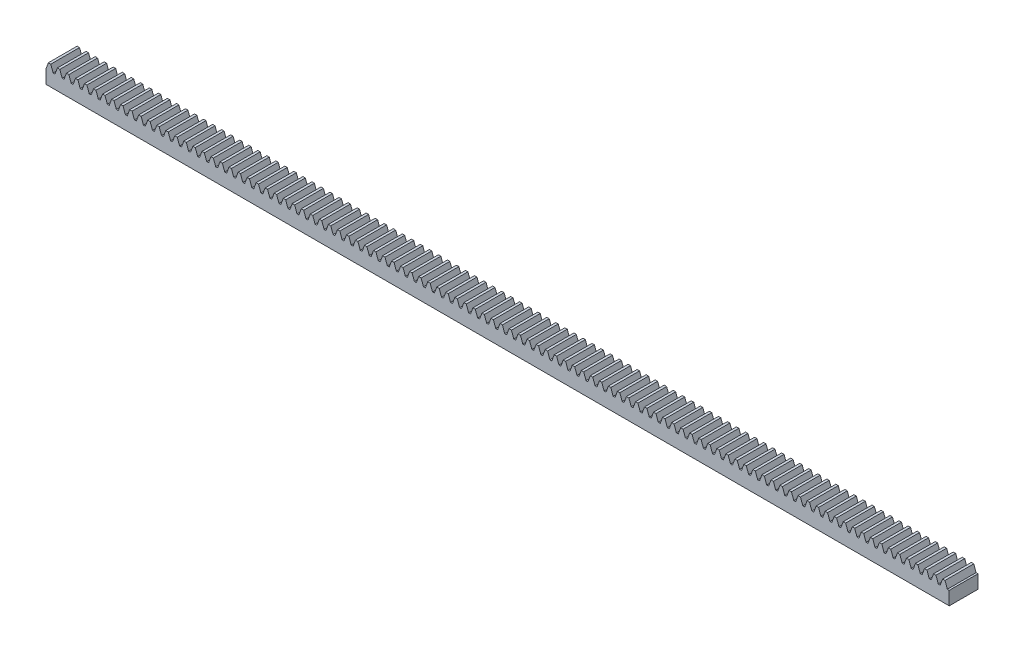
SolidWorks part; units mm, degrees
ref_plane "前视基准面" through (0, 0, 0) normal (0, 0, 1) x (1, 0, 0)
ref_plane "上视基准面" through (0, 0, 0) normal (0, 1, 0) x (1, 0, 0)
ref_plane "右视基准面" through (0, 0, 0) normal (1, 0, 0) x (0, 0, -1)
sketch "草图1" plane through (0, 0, 0) normal (0, 0, 1) x (1, 0, 0)
  line L1 (0, 0) -> (628.3185, 0)
  line L2 (0, 0) -> (0, -9.35)
  line L3 (0, -9.35) -> (628.3185, -9.35)
  line L4 (628.3185, 0) -> (628.3185, -9.35)
  dimension "D1" = 9.35
  dimension "L" = 628.3185
extrude "拉伸1" add sketch "草图1" along normal blind 20
sketch "草图2" plane through (0, 0, 20) normal (0, 0, 1) x (1, 0, 0)
  line L0 (0, 0) -> (1.6379, 4.5)
  line L1 (1.6379, 4.5) -> (3.3236, 4.5)
  line L2 (3.3236, 4.5) -> (4.9614, 0)
  line L3 (628.3185, 0) -> (0, 0) construction
  line L4 (0, 0) -> (4.9614, 0)
  line L5 (0.9099, 2.5) -> (4.0515, 2.5) construction
  dimension "D2" = 70
  dimension "alpha" = 110
  dimension "ha" = 2
  dimension "hf" = 2.5
  dimension "S" = 3.1416
extrude "拉伸2" add sketch "草图2" against normal up to surface (20 mm away) up to face at (314.1593, -4.675, 0)
pattern_linear "阵列(线性)1" count 100 spacing 6.2832 along (1, 0, 0) of "拉伸2"
equation "\"d\"=\"S@草图2\" * 2"
equation "\"z\"= int(  \"L@草图1\" / (  \"S@草图2\" * 2 ) + 0.5 )"
